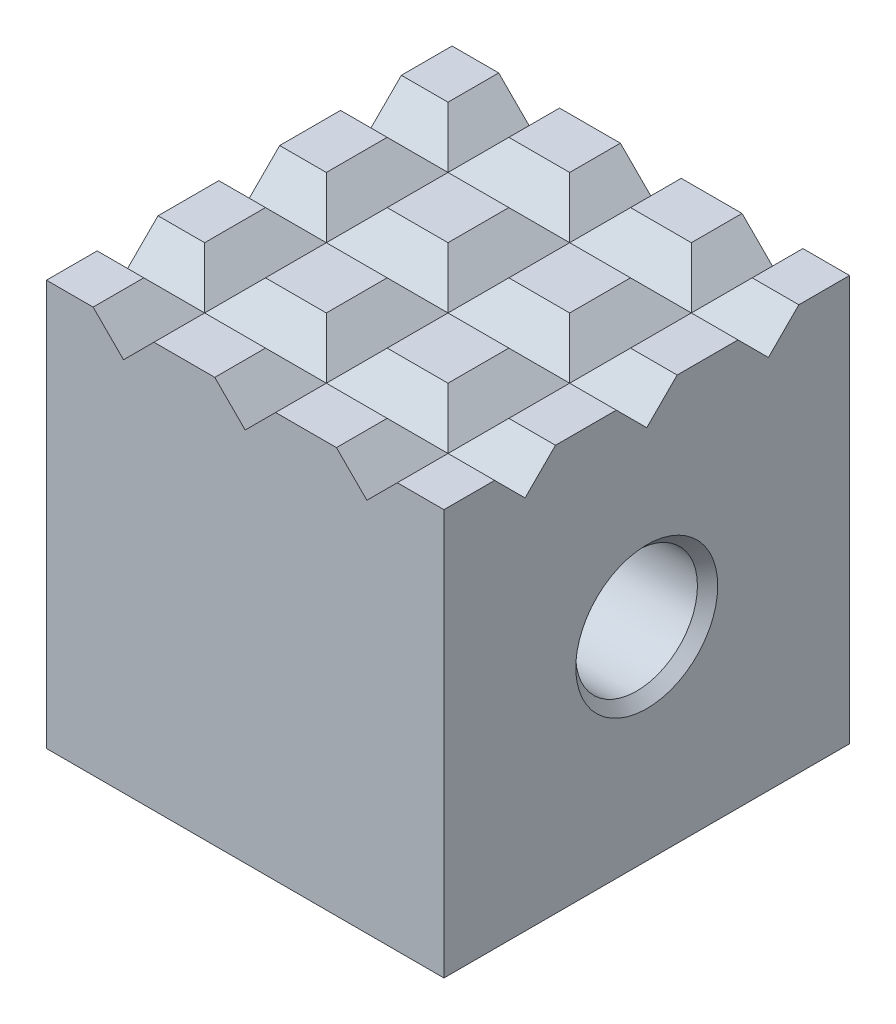
SolidWorks part; units mm, degrees
ref_plane "Front Plane" through (0, 0, 0) normal (0, 0, 1) x (1, 0, 0)
ref_plane "Top Plane" through (0, 0, 0) normal (0, 1, 0) x (1, 0, 0)
ref_plane "Right Plane" through (0, 0, 0) normal (1, 0, 0) x (0, 0, -1)
sketch "Sketch1" plane through (0, 0, 0) normal (1, 0, 0) x (0, 0, -1)
  line L0 (-10, 8.5) -> (10, 8.5) construction
  line L1 (-10, 10) -> (10, 10) construction
  line L2 (-10, 10) -> (-10, -10)
  line L3 (-10, -10) -> (10, -10)
  line L4 (10, 10) -> (10, -10)
  line L5 (-10, 10) -> (10, -10) construction
  line L6 (-10, -10) -> (10, 10) construction
  line L7 (0, 0) -> (0, 10) construction
  line L8 (0, 8.5) -> (-1.5, 10)
  line L9 (-7.5, 10) -> (-6, 8.5)
  line L10 (-6, 8.5) -> (-4.5, 10)
  line L11 (-4.5, 10) -> (-1.5, 10)
  line L12 (-7.5, 10) -> (-10, 10)
  line L13 (0, 8.5) -> (1.5, 10)
  line L14 (4.5, 10) -> (1.5, 10)
  line L15 (6, 8.5) -> (4.5, 10)
  line L16 (7.5, 10) -> (6, 8.5)
  line L17 (7.5, 10) -> (10, 10)
  circle A0 centre (0, 0) radius 3
  point P0 (0, 0)
  dimension "D3" = 6
  dimension "D1" = 20
  dimension "D2" = 20
  dimension "D4" = 1.5
  dimension "D5" = 6
  dimension "D6" = 45
  dimension "D7" = 90
  dimension "D8" = 2.5
extrude "Boss-Extrude1" add sketch "Sketch1" along normal mid plane 19.6
sketch "Sketch2" plane through (0, 0, 0) normal (0, 0, 1) x (1, 0, 0)
  line L0 (0, 0) -> (0, 10) construction
  line L1 (9.8, 10) -> (-9.8, 10) construction
  line L2 (-9.8, 10) -> (9.8, 10) construction
  line L3 (-9.8, 8.5) -> (9.8, 8.5) construction
  line L4 (-9.8, 10) -> (-9.8, -10) construction
  line L5 (9.8, 10) -> (9.8, -10) construction
  line L6 (0, 8.5) -> (-1.5, 10)
  line L7 (-4.5, 10) -> (-6, 8.5)
  line L8 (-6, 8.5) -> (-7.5, 10)
  line L9 (-7.5, 10) -> (-4.5, 10)
  line L10 (-1.5, 10) -> (1.5, 10)
  line L11 (0, 8.5) -> (1.5, 10)
  line L12 (4.5, 10) -> (6, 8.5)
  line L13 (7.5, 10) -> (4.5, 10)
  line L14 (6, 8.5) -> (7.5, 10)
  dimension "D1" = 1.5
  dimension "D2" = 45
  dimension "D3" = 6
  dimension "D4" = 90
  dimension "D5" = 2.3
extrude "Cut-Extrude1" cut sketch "Sketch2" against normal through all and the other way through all contours L9 L8 L7 | L6 L11 L10 | L12 L14 L13
chamfer "Chamfer1" distance 0.5 angle 45 2 edges at (-9.8, 0, -3) (9.8, 0, -3)
